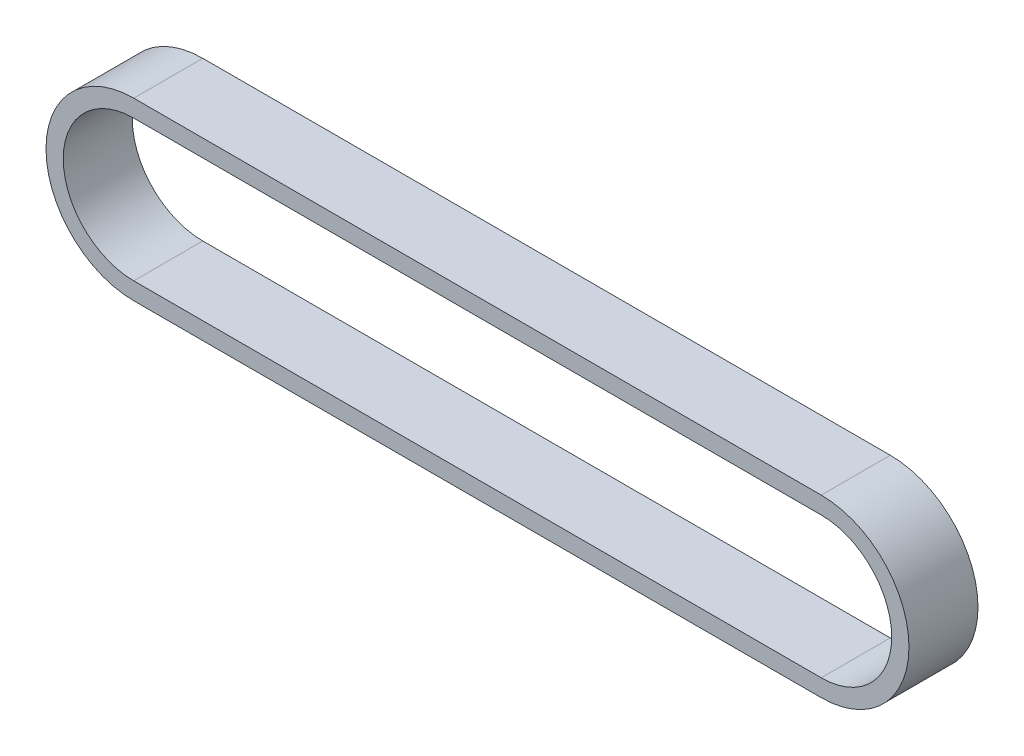
SolidWorks part; units mm, degrees
ref_plane "Front Plane" through (0, 0, 0) normal (0, 0, 1) x (1, 0, 0)
ref_plane "Top Plane" through (0, 0, 0) normal (0, 1, 0) x (1, 0, 0)
ref_plane "Right Plane" through (0, 0, 0) normal (1, 0, 0) x (0, 0, -1)
sketch "Sketch4" plane through (0, 0, 0) normal (0, 0, 1) x (1, 0, 0)
  line L0 (0, 0) -> (59.75, 0) construction
  line L1 (0, 6.125) -> (59.75, 6.125)
  line L2 (0, -6.125) -> (59.75, -6.125)
  line L3 (0, 0) -> (59.75, 0) construction
  line L4 (0, 7.625) -> (59.75, 7.625)
  line L5 (0, -7.625) -> (59.75, -7.625)
  arc A0 (0, 6.125) -> (0, -6.125) centre (0, 0) ccw
  arc A1 (59.75, -6.125) -> (59.75, 6.125) centre (59.75, 0) ccw
  arc A2 (0, 7.625) -> (0, -7.625) centre (0, 0) ccw
  arc A3 (59.75, -7.625) -> (59.75, 7.625) centre (59.75, 0) ccw
  point P3 (29.875, 0)
  point P10 (29.875, 0)
  dimension "D1" = 59.75
  dimension "D2" = 6.125
  dimension "D3" = 1.5
extrude "Boss-Extrude1" add sketch "Sketch4" along normal blind 6
